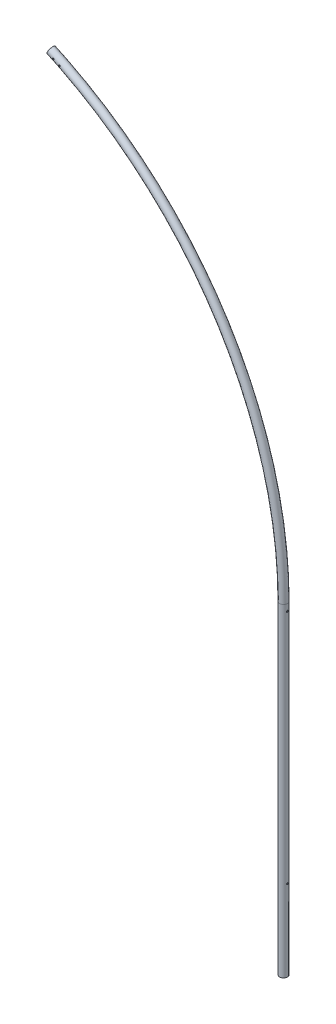
SolidWorks part; units mm, degrees
material "Galvanized Steel"
ref_plane "Front Plane" through (0, 0, 0) normal (0, 0, 1) x (1, 0, 0)
ref_plane "Top Plane" through (0, 0, 0) normal (0, 1, 0) x (1, 0, 0)
ref_plane "Right Plane" through (0, 0, 0) normal (1, 0, 0) x (0, 0, -1)
sketch "Sketch1" plane through (0, 0, 0) normal (0, 0, 1) x (1, 0, 0)
  line L0 (0, 0) -> (0, 1219.2)
  arc A0 (0, 1219.2) -> (-884.5741, 2594.4245) centre (-1511.3, 1219.2) ccw
  dimension "D1" = 65.5
  dimension "D2" = 1219.2
  dimension "D4" = 1375.2245
  dimension "D3" = 1635.1494
  dimension "D5" = 884.5741
sketch "Sketch2" plane through (0, 0, 0) normal (0, 1, 0) x (1, 0, 0)
  line L0 (0, 0) -> (-14.7701, 0) construction
  circle A0 centre (-14.7701, 0) radius 14.7701
  circle A1 centre (-14.7701, 0) radius 13.3223
sweep "Sweep1" add profiles "Sketch2" path "Sketch1"
sketch "Sketch5" plane through (0, 0, 0) normal (0, -1, 0) x (1, 0, 0)
  point P0 (-14.7701, 0)
sketch "Sketch6" plane through (-1711.472, 779.9627, 0) normal (-0.91, 0.4147, 0) x (0, 0, 1)
  point P1 (0, 1979.2288)
sketch "Sketch7" plane through (0, 0, 0) normal (1, 0, 0) x (0, 0, -1)
  line L0 (-14.7701, 1219.2) -> (14.7701, 1219.2) construction
  circle A0 centre (0, 304.8) radius 3.175
  circle A1 centre (0, 1193.8) radius 3.175
  dimension "D1" = 304.8
  dimension "D2" = 25.4
extrude "Cut-Extrude1" cut sketch "Sketch7" against normal blind 31.75
sketch "Sketch8" plane through (0, 0, 0) normal (0, 0, 1) x (1, 0, 0)
  line L0 (-885.1745, 2593.107) -> (-896.2238, 2568.8615) construction
  circle A0 centre (-867.8818, 2569.8022) radius 3.175
  circle A1 centre (-845.0232, 2558.7108) radius 3.175
  dimension "D1" = 25.4
  dimension "D2" = 50.8
extrude "Cut-Extrude2" cut sketch "Sketch8" against normal through all and the other way through all
